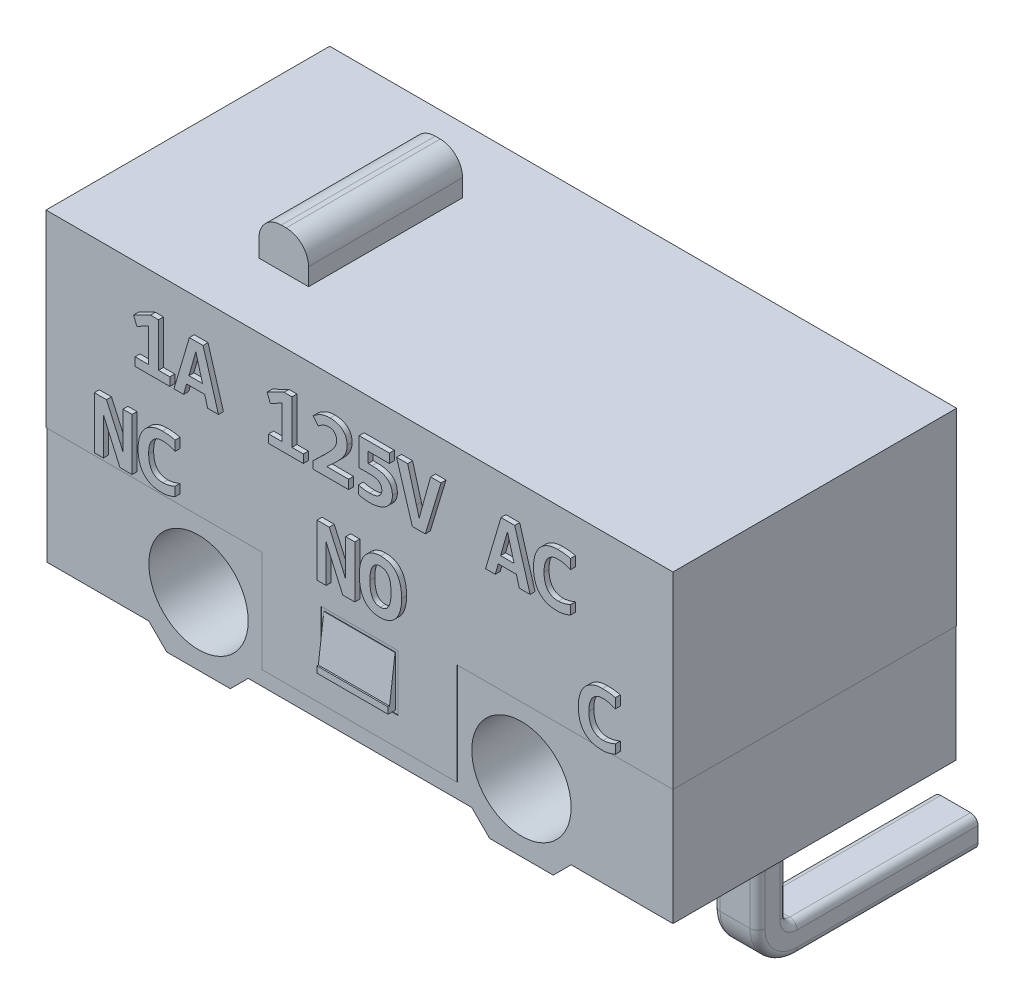
SolidWorks part; units mm, degrees
ref_plane "Ön Düzlem" through (0, 0, 0) normal (0, 0, 1) x (1, 0, 0)
ref_plane "Üst Düzlem" through (0, 0, 0) normal (0, 1, 0) x (1, 0, 0)
ref_plane "Sağ Düzlem" through (0, 0, 0) normal (1, 0, 0) x (0, 0, -1)
sketch "Çizim1" plane through (0, 0, 0) normal (0, 0, 1) x (1, 0, 0)
  line L0 (-2.25, -2.89) -> (2.25, -2.89)
  line L1 (-6.3, 3.25) -> (6.3, 3.25)
  line L2 (-6.3, 3.25) -> (-6.3, -2.89)
  line L3 (-3.89, -3.25) -> (-2.61, -3.25)
  line L4 (6.3, 3.25) -> (6.3, -2.89)
  line L5 (4.25, -2.89) -> (6.3, -2.89)
  line L6 (2.61, -3.25) -> (3.89, -3.25)
  line L9 (-6.3, -2.89) -> (-4.25, -2.89)
  line L10 (-4.25, -2.89) -> (-3.89, -3.25)
  line L11 (-2.25, -2.89) -> (-2.61, -3.25)
  line L12 (4.25, -2.89) -> (3.89, -3.25)
  line L13 (2.25, -2.89) -> (2.61, -3.25)
  circle A0 centre (-3.25, -1.89) radius 1
  circle A1 centre (3.25, -1.89) radius 1
  dimension "D1" = 12.6
extrude "Yükseklik-Ekstrüzyon1" add sketch "Çizim1" along normal blind 5.7
sketch "Çizim2" plane through (0, 0, 5.7) normal (0, 0, 1) x (1, 0, 0)
  line L0 (-6.3, -0.5414) -> (-1.959, -0.5414)
  line L1 (-6.3, 3.25) -> (-6.3, -2.89) construction
  line L2 (-1.959, -0.5414) -> (-1.959, -2.5891)
  line L3 (-1.959, -2.5891) -> (1.959, -2.5891)
  line L4 (1.959, -0.5414) -> (1.959, -2.5891)
  line L5 (6.3, -0.5414) -> (1.959, -0.5414)
  line L6 (-6.3, -0.5414) -> (-6.3, 3.25)
  line L7 (-6.3, 3.25) -> (6.3, 3.25)
  line L8 (6.3, 3.25) -> (6.3, -0.5414)
  line L10 (-0.7777, -0.8894) -> (0.7777, -0.8894)
  line L11 (-0.7777, -0.8894) -> (-0.7777, -2.0181)
  line L12 (-0.7777, -2.0181) -> (0.7777, -2.0181)
  line L13 (0.7777, -0.8894) -> (0.7777, -2.0181)
extrude "Yükseklik-Ekstrüzyon2" add sketch "Çizim2" along normal blind 0.01
sketch "Çizim3" plane through (6.3, 0, 0) normal (1, 0, 0) x (0, 0, -1)
  line L0 (-5.71, -0.5414) -> (0, -0.5414)
  line L1 (0, -2.89) -> (0, 3.25) construction
  line L2 (0, -0.5414) -> (0, 3.25)
  line L3 (0, 3.25) -> (-5.71, 3.25)
  line L10 (0, -2.89) -> (0, 3.25)
  line L11 (0, 3.25) -> (-5.71, 3.25)
  line L12 (-5.71, 3.25) -> (-5.71, -0.5414)
  line L13 (-5.71, -0.5414) -> (-5.7, -0.5414)
  line L14 (-5.7, -0.5414) -> (-5.7, -2.89)
  line L15 (-5.7, -2.89) -> (0, -2.89)
  line L18 (-5.71, 3.25) -> (-5.71, -0.5414)
  dimension "D1" = 0
extrude "Yükseklik-Ekstrüzyon3" add sketch "Çizim3" along normal blind 0.01
mirror "Aynalama1" about plane through (0, 0, 0) normal (1, 0, 0) of "Yükseklik-Ekstrüzyon3"
sketch "Çizim4" plane through (0, 0, 5.7) normal (0, 0, 1) x (1, 0, 0)
  line L1 (-0.7168, -0.9504) -> (0.7168, -0.9504)
  line L2 (-0.7168, -0.9504) -> (-0.7168, -1.9571)
  line L3 (-0.7168, -1.9571) -> (0.7168, -1.9571)
  line L4 (0.7168, -0.9504) -> (0.7168, -1.9571)
  line L5 (-0.7168, -0.9504) -> (0.7168, -1.9571) construction
  line L6 (-0.7168, -1.9571) -> (0.7168, -0.9504) construction
  point P0 (0, -1.4538)
extrude "Yükseklik-Ekstrüzyon4" add sketch "Çizim4" along normal blind 0.15
sketch "Çizim5" plane through (0.7168, 0, 0) normal (1, 0, 0) x (0, 0, -1)
  line L0 (-5.85, -1.8289) -> (-5.8216, -1.8289)
  line L1 (-5.85, -1.9571) -> (-5.85, -0.9504) construction
  line L2 (-5.8216, -1.8289) -> (-5.71, -0.9504)
  line L3 (-5.71, -2.5891) -> (-5.71, -0.5414) construction
  line L4 (-5.85, -0.9504) -> (-5.7, -0.9504) construction
  line L5 (-5.71, -0.9504) -> (-5.85, -0.9504)
  line L6 (-5.85, -0.9504) -> (-5.85, -1.8289)
extrude "Kes-Ekstrüzyon1" cut sketch "Çizim5" against normal blind 2.15
sketch "Çizim7" plane through (0, 3.25, 0) normal (0, 1, 0) x (1, 0, 0)
  line L4 (-3.3299, -1.305) -> (-2.3299, -1.305)
  line L5 (-3.3299, -1.305) -> (-3.3299, -4.405)
  line L6 (-3.3299, -4.405) -> (-2.3299, -4.405)
  line L7 (-2.3299, -1.305) -> (-2.3299, -4.405)
  line L8 (-3.3299, -1.305) -> (-2.3299, -4.405) construction
  line L9 (-3.3299, -4.405) -> (-2.3299, -1.305) construction
  point P6 (-2.8299, -2.855)
extrude "Yükseklik-Ekstrüzyon5" add sketch "Çizim7" along normal blind 0.8
fillet "Radyus1" radius 0.45 2 edges at (-3.3299, 4.05, 2.855) (-2.3299, 4.05, 2.855)
sketch "Çizim8" plane through (0, -2.89, 0) normal (0, -1, 0) x (-1, 0, 0)
  line L2 (5.45, -3.15) -> (4.55, -3.15)
  line L3 (5.45, -3.15) -> (5.45, -2.55)
  line L4 (5.45, -2.55) -> (4.55, -2.55)
  line L5 (4.55, -3.15) -> (4.55, -2.55)
  line L6 (5.45, -3.15) -> (4.55, -2.55) construction
  line L7 (5.45, -2.55) -> (4.55, -3.15) construction
  point P2 (5, -2.85)
ref_plane "Düzlem1" through (-5, 0, 0) normal (1, 0, 0) x (0, 0, -1)
sketch "Çizim10" plane through (-5, 0, 0) normal (1, 0, 0) x (0, 0, -1)
  line L1 (-2.85, -2.89) -> (-2.85, -4.75)
  line L3 (-2.35, -5.25) -> (1.29, -5.25)
  arc A0 (-2.85, -4.75) -> (-2.35, -5.25) centre (-2.35, -4.75) ccw
  dimension "D1" = 0.5
sweep "Süpür1" add profiles "Çizim8" path "Çizim10"
sketch "Çizim12" plane through (0, -2.89, 0) normal (0, -1, 0) x (1, 0, 0)
  line L3 (-0.45, 3.15) -> (0.45, 3.15)
  line L4 (-0.45, 3.15) -> (-0.45, 2.55)
  line L5 (-0.45, 2.55) -> (0.45, 2.55)
  line L6 (0.45, 3.15) -> (0.45, 2.55)
  line L7 (-0.45, 3.15) -> (0.45, 2.55) construction
  line L8 (-0.45, 2.55) -> (0.45, 3.15) construction
  point P5 (0, 2.85)
sketch "Çizim13" plane through (0, 0, 0) normal (1, 0, 0) x (0, 0, -1)
  line L1 (-2.85, -2.89) -> (-2.85, -4.75)
  line L2 (-2.35, -5.25) -> (1.29, -5.25)
  line L3 (1.29, -4.95) -> (1.29, -5.55) construction
  arc A0 (-2.85, -4.75) -> (-2.35, -5.25) centre (-2.35, -4.75) ccw
  dimension "D1" = 0.5
sweep "Süpür2" add profiles "Çizim12" path "Çizim13"
mirror "Aynalama2" about plane through (0, 0, 0) normal (1, 0, 0) of "Süpür1"
fillet "Radyus2" radius 0.15 36 edges at (-5.45, -3.82, 2.55) (-5.45, -4.8914, 2.4914) (-4.55, -3.82, 2.55) (-4.55, -4.8914, 2.4914) (-0.45, -3.82, 2.55) (-0.45, -4.8914, 2.4914) (0.45, -3.82, 2.55) (0.45, -4.8914, 2.4914) (4.55, -3.82, 2.55) (4.55, -4.8914, 2.4914) (5.45, -3.82, 2.55) (5.45, -4.8914, 2.4914) (5.45, -3.82, 3.15) (5.45, -5.3157, 2.9157) (0.45, -3.82, 3.15) (0.45, -5.3157, 2.9157) (-4.55, -3.82, 3.15) (-4.55, -5.3157, 2.9157) (4.55, -3.82, 3.15) (4.55, -5.3157, 2.9157) (-0.45, -3.82, 3.15) (-0.45, -5.3157, 2.9157) (-5.45, -3.82, 3.15) (-5.45, -5.3157, 2.9157) (-5.45, -4.95, 0.53) (-4.55, -4.95, 0.53) (-0.45, -4.95, 0.53) (0.45, -4.95, 0.53) (4.55, -4.95, 0.53) (5.45, -4.95, 0.53) (5.45, -5.55, 0.53) (0.45, -5.55, 0.53) (-4.55, -5.55, 0.53) (4.55, -5.55, 0.53) (-0.45, -5.55, 0.53) (-5.45, -5.55, 0.53)
sketch "Çizim14" plane through (0, 0, 5.71) normal (0, 0, 1) x (1, 0, 0)
  text T0 "1A 125V AC" font "Consolas" height in points 4
  text T1 "C" font "Consolas" height in points 4
  text T2 "NO" font "Consolas" height in points 4
  text T3 "NC" font "Consolas" height in points 4
extrude "Yükseklik-Ekstrüzyon6" add sketch "Çizim14" along normal blind 0.1
